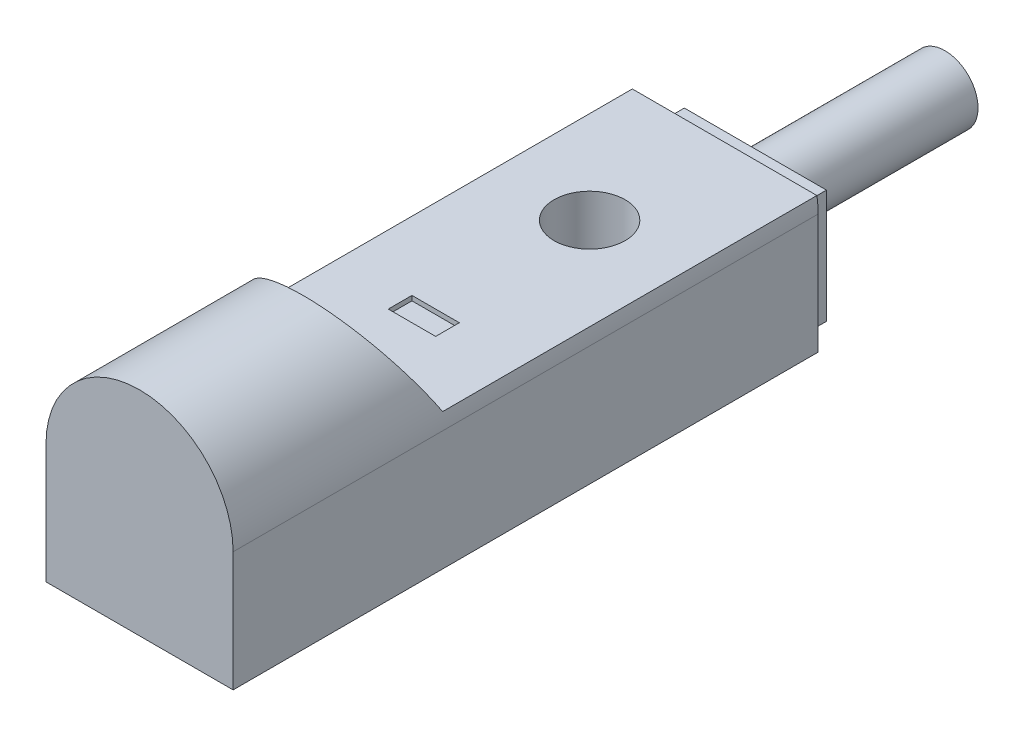
SolidWorks part; units mm, degrees
ref_plane "Plan de face" through (0, 0, 0) normal (0, 0, 1) x (1, 0, 0)
ref_plane "Plan de dessus" through (0, 0, 0) normal (0, 1, 0) x (1, 0, 0)
ref_plane "Plan de droite" through (0, 0, 0) normal (1, 0, 0) x (0, 0, -1)
sketch "Esquisse1" plane through (0, 0, 0) normal (0, 0, 1) x (1, 0, 0)
  line L0 (0, 0) -> (0, 5.05) construction
  line L1 (-3.95, 5.05) -> (-3.95, 0)
  line L2 (-3.95, 0) -> (3.95, 0)
  line L3 (3.95, 5.05) -> (3.95, 0)
  arc A0 (-3.95, 5.05) -> (3.95, 5.05) centre (0, 5.05) cw
  point P7 (0, 9)
  dimension "D2" = 9
  dimension "D1" = 7.9
extrude "Boss.-Extru.1" add sketch "Esquisse1" against normal blind 24.7
sketch "Esquisse2" plane through (0, 0, 0) normal (1, 0, 0) x (0, 0, -1)
  line L0 (6.9, 9) -> (8.9, 5.7)
  line L1 (8.9, 5.7) -> (24.7, 5.7)
  line L2 (24.7, 5.05) -> (24.7, 9) construction
  line L3 (24.7, 5.7) -> (24.7, 9)
  line L4 (24.7, 9) -> (6.9, 9)
  line L5 (24.7, 9) -> (0, 9) construction
  dimension "D1" = 6.9
  dimension "D2" = 8.9
  dimension "D3" = 5.7
extrude "Enlèv. mat.-Extru.1" cut sketch "Esquisse2" against normal through all both and the other way through all
hole_wizard "Dégagement M31" positions "Esquisse3" profile "Esquisse4" hole size "M3" standard "ISO" end condition through all
sketch "Esquisse3" plane through (0, 5.7, 0) normal (0, 1, 0) x (1, 0, 0)
  point P0 (0, 19)
  dimension "D1" = 19
sketch "Esquisse4" plane through (0, 5.7, -19) normal (1, 0, 0) x (0, 0, 1)
  line L0 (0, 0) -> (0, 5.7)
  line L1 (0, 5.7) -> (1.5, 5.7)
  line L2 (1.5, 5.7) -> (1.5, 0)
  line L5 (1.5, 0) -> (0, 0)
  line L11 (0, -6.35) -> (0, 107.95) construction
  dimension "Diamètre du perçage jusqu'au prochain" = 3
  dimension "Profondeur du perçage jusqu'au prochain" = 5.7
sketch "Esquisse5" plane through (0, 0, -24.7) normal (0, 0, -1) x (-1, 0, 0)
  line L0 (3.95, 0) -> (-3.95, 0) construction
  line L1 (-3, 4.8) -> (3, 4.8)
  line L2 (-3, 4.8) -> (-3, 0)
  line L3 (-3, 0) -> (3, 0)
  line L4 (3, 4.8) -> (3, 0)
  point P4 (0, 0)
  dimension "D1" = 4.8
  dimension "D2" = 6
extrude "Boss.-Extru.2" add sketch "Esquisse5" along normal blind 1.3
sketch "Esquisse6" plane through (0, 0, -26) normal (0, 0, -1) x (-1, 0, 0)
  circle A0 centre (0, 3) radius 1.4
  dimension "D2" = 2.8
  dimension "D1" = 3
extrude "Boss.-Extru.3" add sketch "Esquisse6" along normal blind 8
sketch "Esquisse7" plane through (0, 5.7, 0) normal (0, 1, 0) x (1, 0, 0)
  line L1 (-1, 12.5) -> (1, 12.5)
  line L2 (-1, 12.5) -> (-1, 11.5)
  line L3 (-1, 11.5) -> (1, 11.5)
  line L4 (1, 12.5) -> (1, 11.5)
  point P4 (0, 11.5)
  point P6 (1, 12)
  dimension "D1" = 12
  dimension "D2" = 2
  dimension "D3" = 1
extrude "Enlèv. mat.-Extru.2" cut sketch "Esquisse7" against normal blind 0.2
